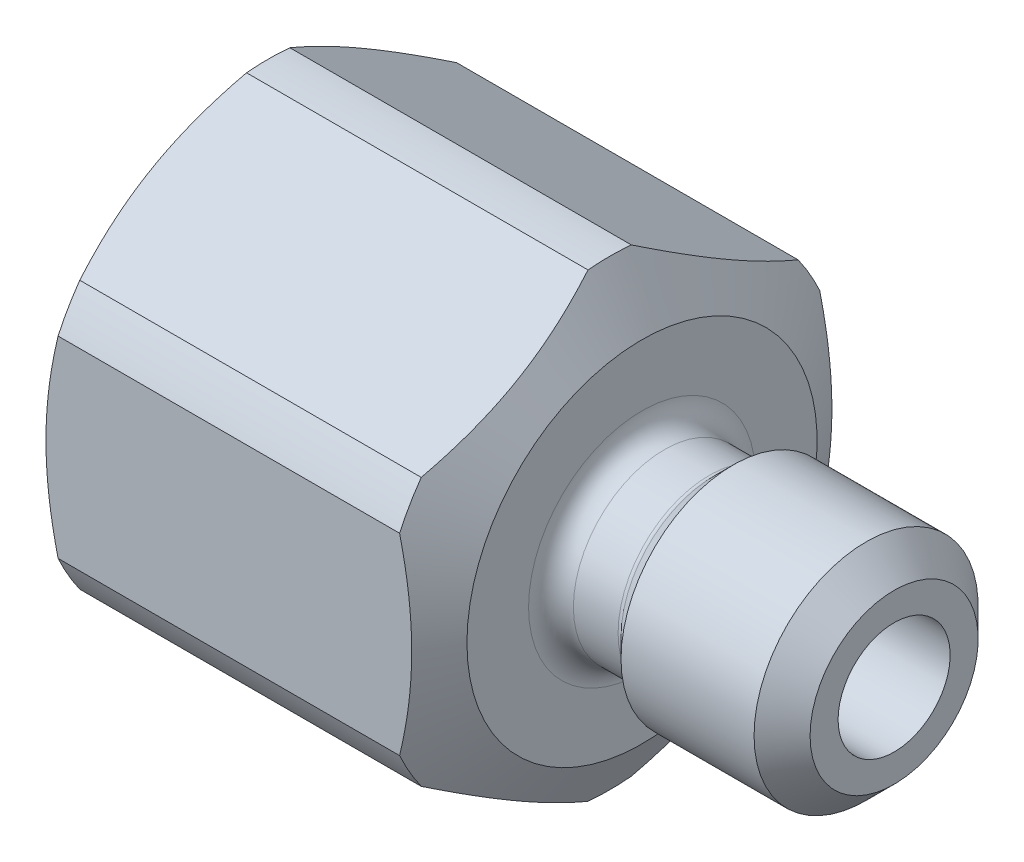
SolidWorks part; units mm, degrees
material "Сталь 20 ГОСТ 1050-2013"
ref_plane "Спереди" through (0, 0, 0) normal (0, 0, 1) x (1, 0, 0)
ref_plane "Сверху" through (0, 0, 0) normal (0, 1, 0) x (1, 0, 0)
ref_plane "Справа" through (0, 0, 0) normal (1, 0, 0) x (0, 0, -1)
sketch "Эскиз1" plane through (0, 0, 0) normal (0, 0, 1) x (1, 0, 0)
  line L0 (-14.4649, 0) -> (43.4661, 0) construction
  line L1 (30.6, 6.5) -> (33.7929, 6.5)
  line L2 (34.1464, 6.6464) -> (35.5, 8)
  line L3 (35.5, 8) -> (45, 8)
  line L4 (47, 6) -> (47, 4)
  line L5 (47, 4) -> (26, 4)
  line L6 (24, 6) -> (24, 8.9)
  line L7 (22.4, 10.5) -> (19.2071, 10.5)
  line L8 (18.8536, 10.3536) -> (8.5, 0)
  line L10 (0, 0) -> (0, 12.5)
  line L11 (2.3094, 16.5) -> (26.6906, 16.5)
  line L12 (29, 12.5) -> (29, 8.1)
  line L13 (0, 0) -> (8.5, 0)
  line L14 (45, 8) -> (47, 6)
  line L15 (26, 4) -> (24, 6)
  line L16 (2.3094, 16.5) -> (0, 12.5)
  line L17 (26.6906, 16.5) -> (29, 12.5)
  arc A0 (30.6, 6.5) -> (29, 8.1) centre (30.6, 8.1) cw
  arc A1 (33.7929, 6.5) -> (34.1464, 6.6464) centre (33.7929, 7) ccw
  arc A2 (24, 8.9) -> (22.4, 10.5) centre (22.4, 8.9) ccw
  arc A3 (19.2071, 10.5) -> (18.8536, 10.3536) centre (19.2071, 10) ccw
  point P7 (47, 8)
  point P9 (24, 4)
  point P19 (29, 6.5)
  point P22 (34, 6.5)
  point P27 (19, 10.5)
  dimension "D7" = 1.6
  dimension "D8" = 0.5
  dimension "D9" = 1.6
  dimension "D11" = 0.5
  dimension "D1" = 16
  dimension "D2" = 2
  dimension "D3" = 45
  dimension "D4" = 45
  dimension "D5" = 13
  dimension "D6" = 5
  dimension "D10" = 5
  dimension "D12" = 21
  dimension "D13" = 8
  dimension "D14" = 5
  dimension "D15" = 18
  dimension "D16" = 33
  dimension "D17" = 24
  dimension "D18" = 2
  dimension "D19" = 45
  dimension "D20" = 25
  dimension "D21" = 30
  dimension "D22" = 30
revolve "Повернуть1" add sketch "Эскиз1" angle 360 about L0
cosmetic thread "Условное изображение резьбы1" [suppressed] parameters "D2"=10.072
cosmetic thread "Условное изображение резьбы2" parameters "D1"=5, "D2"=13.797
hole_wizard "Отверстие обработанное метчиком 1" positions "Эскиз2" profile "Эскиз3" tap size "M20" standard "ISO"
sketch "Эскиз2" plane through (0, 0, 0) normal (-1, 0, 0) x (0, 0, 1)
  point P0 (0, 0)
sketch "Эскиз3" plane through (0, 0, 0) normal (0, 1, 0) x (0, 0, 1)
  line L0 (0, 0) -> (0, 23.999)
  line L1 (0, 23.999) -> (8.75, 23.999)
  line L2 (8.75, 23.999) -> (8.75, 2.5)
  line L3 (8.75, 2.5) -> (11.25, 0)
  line L5 (11.25, 0) -> (0, 0)
  line L6 (-8.75, 2.5) -> (-11.25, 0) construction
  line L10 (0, 23.999) -> (-8.75, 23.999) construction
  line L11 (0, -6.35) -> (0, 107.95) construction
  dimension "Диаметр сверла" = 17.5
  dimension "Глубина сверла" = 23.999
  dimension "Диаметр передней зенковки" = 22.5
  dimension "Угол передней зенковки" = 90
  dimension "Угол заточки сверла" = 180
cosmetic thread "Отверстие резьбы1" parameters "D1"=17.25, "D2"=20
sketch "Эскиз4" plane through (0, 0, 0) normal (-1, 0, 0) x (0, 0, 1)
  line L1 (0, 17.3205) -> (-15, 8.6603)
  line L2 (-15, 8.6603) -> (-15, -8.6603)
  line L3 (-15, -8.6603) -> (0, -17.3205)
  line L4 (0, -17.3205) -> (15, -8.6603)
  line L5 (15, -8.6603) -> (15, 8.6603)
  line L6 (15, 8.6603) -> (0, 17.3205)
  circle A0 centre (0, 0) radius 15 construction
  dimension "D1" = 30
extrude "Вырез-Вытянуть1" cut sketch "Эскиз4" against normal through all flip side to cut
